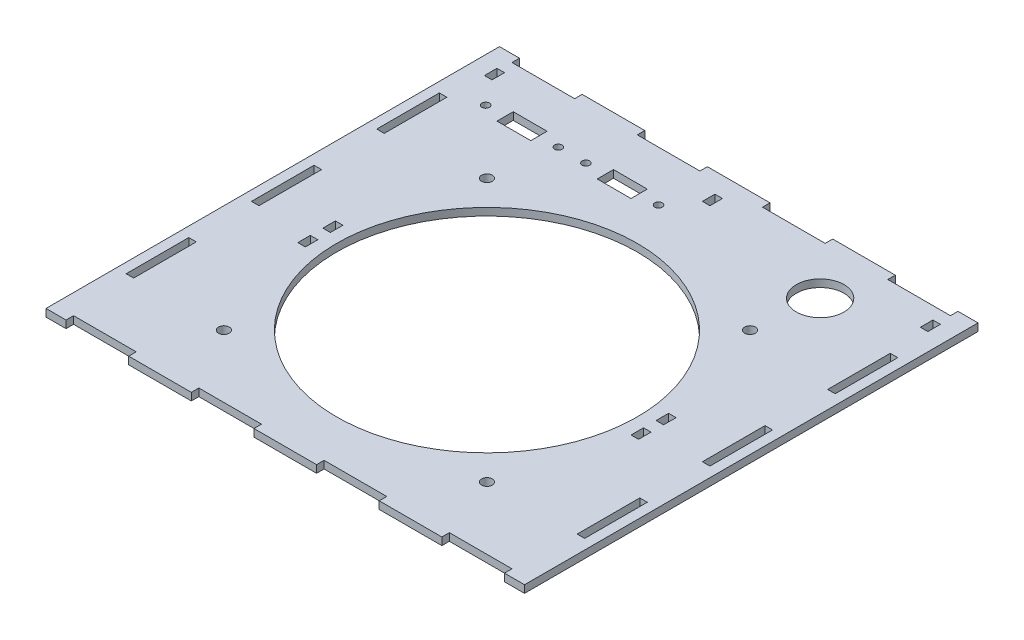
SolidWorks part; units mm, degrees
material "Buk"
ref_plane "Přední rovina" through (0, 0, 0) normal (0, 0, 1) x (1, 0, 0)
ref_plane "Horní rovina" through (0, 0, 0) normal (0, 1, 0) x (1, 0, 0)
ref_plane "Pravá rovina" through (0, 0, 0) normal (1, 0, 0) x (0, 0, -1)
sketch "Skica1" plane through (0, 0, 0) normal (0, 1, 0) x (1, 0, 0)
  line L0 (-95.5, -87.5) -> (95.5, 87.5) construction
  line L1 (-95.5, 87.5) -> (95.5, 87.5)
  line L2 (-95.5, 87.5) -> (-95.5, -87.5)
  line L3 (-95.5, -87.5) -> (95.5, -87.5)
  line L4 (95.5, 87.5) -> (95.5, -87.5)
  dimension "D1" = 175
  dimension "D2" = 191
extrude "Přidat vysunutím1" add sketch "Skica1" along normal blind 3
sketch "Skica13" plane through (0, 0, 0) normal (0, 1, 0) x (1, 0, 0)
  line L0 (95.5, 87.5) -> (-95.5, 87.5) construction
  line L1 (-62.5, 87.5) -> (-37.5, 87.5)
  line L2 (-62.5, 87.5) -> (-62.5, 90.5)
  line L3 (-62.5, 90.5) -> (-37.5, 90.5)
  line L4 (-37.5, 87.5) -> (-37.5, 90.5)
  line L6 (0, 0) -> (0, 52.1554) construction
  line L7 (-12.5, 87.5) -> (12.5, 87.5)
  line L8 (-12.5, 87.5) -> (-12.5, 90.5)
  line L9 (-12.5, 90.5) -> (12.5, 90.5)
  line L10 (12.5, 87.5) -> (12.5, 90.5)
  line L11 (37.5, 87.5) -> (62.5, 87.5)
  line L12 (37.5, 87.5) -> (37.5, 90.5)
  line L13 (37.5, 90.5) -> (62.5, 90.5)
  line L14 (62.5, 87.5) -> (62.5, 90.5)
  line L15 (-37.5, 90.5) -> (-12.5, 90.5) construction
  line L16 (-37.5, -90.5) -> (-12.5, -90.5) construction
  line L17 (62.5, -87.5) -> (62.5, -90.5)
  line L18 (37.5, -90.5) -> (62.5, -90.5)
  line L19 (37.5, -87.5) -> (37.5, -90.5)
  line L20 (37.5, -87.5) -> (62.5, -87.5)
  line L21 (12.5, -87.5) -> (12.5, -90.5)
  line L22 (-12.5, -90.5) -> (12.5, -90.5)
  line L23 (-12.5, -87.5) -> (-12.5, -90.5)
  line L24 (-12.5, -87.5) -> (12.5, -87.5)
  line L25 (-37.5, -87.5) -> (-37.5, -90.5)
  line L26 (-62.5, -90.5) -> (-37.5, -90.5)
  line L27 (-62.5, -87.5) -> (-62.5, -90.5)
  line L28 (-62.5, -87.5) -> (-37.5, -87.5)
  line L29 (-62.5, 90.5) -> (-87.5, 90.5) construction
  line L30 (-95.5, 87.5) -> (-87.5, 87.5)
  line L31 (-95.5, 87.5) -> (-95.5, 90.5)
  line L32 (-95.5, 90.5) -> (-87.5, 90.5)
  line L33 (-87.5, 87.5) -> (-87.5, 90.5)
  line L34 (95.5, -87.5) -> (87.5, -87.5)
  line L35 (87.5, 87.5) -> (87.5, 90.5)
  line L36 (95.5, -87.5) -> (95.5, -90.5)
  line L37 (95.5, -90.5) -> (87.5, -90.5)
  line L38 (95.5, 90.5) -> (87.5, 90.5)
  line L39 (95.5, 87.5) -> (95.5, 90.5)
  line L40 (95.5, 87.5) -> (87.5, 87.5)
  line L41 (87.5, -87.5) -> (87.5, -90.5)
  line L42 (-87.5, -87.5) -> (-87.5, -90.5)
  line L43 (-95.5, -90.5) -> (-87.5, -90.5)
  line L44 (-95.5, -87.5) -> (-95.5, -90.5)
  line L45 (-95.5, -87.5) -> (-87.5, -87.5)
  line L71 (0, 0) -> (-249.3085, 0) construction
  dimension "D1" = 25
  dimension "D2" = 3
  dimension "D3" = 3
extrude "Přidat vysunutím5" add sketch "Skica13" along normal up to surface (3 mm away) up to face at (0, 3, 0)
sketch "Skica14" plane through (0, 0, 0) normal (0, 1, 0) x (1, 0, 0)
  line L0 (95.5, -90.5) -> (95.5, 90.5) construction
  line L1 (85.5, 82.5) -> (88.5, 82.5)
  line L2 (85.5, 82.5) -> (85.5, 77.5)
  line L3 (85.5, 77.5) -> (88.5, 77.5)
  line L4 (88.5, 82.5) -> (88.5, 77.5)
  line L6 (87.5, 87.5) -> (62.5, 87.5) construction
  line L7 (-1.5, 82.5) -> (1.5, 82.5)
  line L8 (-1.5, 82.5) -> (-1.5, 77.5)
  line L9 (-1.5, 77.5) -> (1.5, 77.5)
  line L10 (1.5, 82.5) -> (1.5, 77.5)
  line L12 (0, 0) -> (0, 114.4854) construction
  line L17 (-88.5, 82.5) -> (-88.5, 77.5)
  line L18 (-85.5, 77.5) -> (-88.5, 77.5)
  line L19 (-85.5, 82.5) -> (-85.5, 77.5)
  line L20 (-85.5, 82.5) -> (-88.5, 82.5)
  dimension "D1" = 7
  dimension "D2" = 3
  dimension "D3" = 5
  dimension "D4" = 5
extrude "Odebrat vysunutím7" cut sketch "Skica14" along normal through all
sketch "Skica15" plane through (0, 0, 0) normal (0, 1, 0) x (1, 0, 0)
  line L1 (-91.5, 62.5) -> (-88.5, 62.5)
  line L2 (-91.5, 62.5) -> (-91.5, 37.5)
  line L3 (-91.5, 37.5) -> (-88.5, 37.5)
  line L4 (-88.5, 62.5) -> (-88.5, 37.5)
  line L5 (-95.5, 90.5) -> (-95.5, -90.5) construction
  line L6 (-62.5, 90.5) -> (-62.5, 87.5) construction
  line L8 (-91.5, 62.5) -> (-91.5, 87.5) construction
  line L9 (-62.5, 87.5) -> (-87.5, 87.5) construction
  line L10 (-91.5, 12.5) -> (-88.5, 12.5)
  line L11 (-91.5, 12.5) -> (-91.5, -12.5)
  line L12 (-91.5, -12.5) -> (-88.5, -12.5)
  line L13 (-88.5, 12.5) -> (-88.5, -12.5)
  line L14 (-91.5, -37.5) -> (-88.5, -37.5)
  line L15 (-91.5, -37.5) -> (-91.5, -62.5)
  line L16 (-91.5, -62.5) -> (-88.5, -62.5)
  line L17 (-88.5, -37.5) -> (-88.5, -62.5)
  line L18 (-91.5, 37.5) -> (-91.5, 12.5) construction
  line L19 (91.5, 37.5) -> (91.5, 12.5) construction
  line L20 (91.5, 62.5) -> (91.5, 87.5) construction
  line L21 (88.5, -37.5) -> (88.5, -62.5)
  line L22 (91.5, -62.5) -> (88.5, -62.5)
  line L23 (91.5, -37.5) -> (91.5, -62.5)
  line L24 (91.5, -37.5) -> (88.5, -37.5)
  line L25 (88.5, 12.5) -> (88.5, -12.5)
  line L26 (91.5, -12.5) -> (88.5, -12.5)
  line L27 (91.5, 12.5) -> (91.5, -12.5)
  line L28 (91.5, 12.5) -> (88.5, 12.5)
  line L29 (88.5, 62.5) -> (88.5, 37.5)
  line L30 (91.5, 37.5) -> (88.5, 37.5)
  line L31 (91.5, 62.5) -> (91.5, 37.5)
  line L32 (91.5, 62.5) -> (88.5, 62.5)
  line L73 (0, 0) -> (0, 107.6413) construction
  dimension "D1" = 25
  dimension "D2" = 4
  dimension "D3" = 3
extrude "Odebrat vysunutím8" cut sketch "Skica15" along normal through all
sketch "Skica16" plane through (0, 0, 0) normal (0, 1, 0) x (1, 0, 0)
  line L0 (-65, 0) -> (65, 0) construction
  line L2 (-65, -2.5) -> (-68, -2.5)
  line L3 (-65, -2.5) -> (-65, -7.5)
  line L4 (-65, -7.5) -> (-68, -7.5)
  line L5 (-68, -2.5) -> (-68, -7.5)
  line L6 (-65, -7.5) -> (-65, -12.5) construction
  line L7 (-87.5, -87.5) -> (-62.5, -87.5) construction
  line L10 (-65, -12.5) -> (-68, -12.5)
  line L11 (-65, -12.5) -> (-65, -17.5)
  line L12 (-65, -17.5) -> (-68, -17.5)
  line L13 (-68, -12.5) -> (-68, -17.5)
  line L14 (0, 0) -> (0, -24.7218) construction
  line L15 (65, -7.5) -> (65, -12.5) construction
  line L16 (68, -12.5) -> (68, -17.5)
  line L17 (65, -17.5) -> (68, -17.5)
  line L18 (65, -12.5) -> (65, -17.5)
  line L19 (65, -12.5) -> (68, -12.5)
  line L20 (68, -2.5) -> (68, -7.5)
  line L21 (65, -7.5) -> (68, -7.5)
  line L22 (65, -2.5) -> (65, -7.5)
  line L23 (65, -2.5) -> (68, -2.5)
  line L24 (-91.5, 12.5) -> (-88.5, 12.5) construction
  dimension "D1" = 130
  dimension "D2" = 85
  dimension "D3" = 5
extrude "Odebrat vysunutím9" cut sketch "Skica16" along normal through all
sketch "Skica4" plane through (0, 0, 0) normal (0, 1, 0) x (1, 0, 0)
  line L0 (0, 0) -> (0, 50) construction
  line L1 (-60, 50) -> (60, 50) construction
  line L2 (-60, 50) -> (-60, -70) construction
  line L3 (-60, -70) -> (60, -70) construction
  line L4 (60, 50) -> (60, -70) construction
  line L5 (-60, -70) -> (60, 50) construction
  line L6 (-60, -10) -> (60, -10) construction
  line L7 (60, -70) -> (-60, 50) construction
  line L9 (-68, -2.5) -> (-65, -2.5) construction
  line L10 (-65, -17.5) -> (-68, -17.5) construction
  circle A0 centre (-52.5, -62.5) radius 2.15
  circle A1 centre (52.5, 42.5) radius 2.15
  circle A2 centre (0, -10) radius 60
  circle A3 centre (-52.5, 42.5) radius 2.15
  circle A4 centre (52.5, -62.5) radius 2.15
  dimension "D2" = 105
  dimension "D4" = 4.3
  dimension "D5" = 120
  dimension "D1" = 120
extrude "Odebrat vysunutím5" cut sketch "Skica4" along normal through all
sketch "Skica5" plane through (0, 0, 0) normal (0, 1, 0) x (1, 0, 0)
  line L0 (95.5, -90.5) -> (95.5, 90.5) construction
  line L1 (87.5, 87.5) -> (62.5, 87.5) construction
  circle A0 centre (55.5, 67.5) radius 9.5
  circle A1 centre (55.5, 67.5) radius 11 construction
  dimension "D1" = 19
  dimension "D2" = 22
  dimension "D4" = 20
  dimension "D3" = 40
extrude "Odebrat vysunutím6" cut sketch "Skica5" along normal through all
sketch "Skica17" plane through (0, 0, 0) normal (0, 1, 0) x (1, 0, 0)
  line L0 (-78, 67.5) -> (-49, 67.5) construction
  line L1 (-63.5, 67.5) -> (-63.5, 62.0039) construction
  line L2 (-70.25, 70.75) -> (-56.75, 70.75)
  line L3 (-70.25, 70.75) -> (-70.25, 64.25)
  line L4 (-70.25, 64.25) -> (-56.75, 64.25)
  line L5 (-56.75, 70.75) -> (-56.75, 64.25)
  line L6 (-30.25, 70.75) -> (-16.75, 70.75)
  line L7 (-30.25, 70.75) -> (-30.25, 64.25)
  line L8 (-30.25, 64.25) -> (-16.75, 64.25)
  line L9 (-16.75, 70.75) -> (-16.75, 64.25)
  line L10 (-38, 67.5) -> (-9, 67.5) construction
  line L11 (-23.5, 67.5) -> (-23.5, 62.0039) construction
  line L13 (-43.5, 56.9694) -> (-43.5, 79.8624) construction
  line L14 (-85.5, 82.5) -> (-85.5, 77.5) construction
  line L15 (-1.5, 77.5) -> (-1.5, 82.5) construction
  circle A0 centre (-78, 67.5) radius 1.5
  circle A1 centre (-49, 67.5) radius 1.5
  circle A2 centre (-38, 67.5) radius 1.5
  circle A3 centre (-9, 67.5) radius 1.5
  circle A5 centre (55.5, 67.5) radius 9.5 construction
  point P22 (55.5, 67.5)
  dimension "D1" = 29
  dimension "D2" = 3
  dimension "D6" = 40
  dimension "D3" = 13.5
  dimension "D4" = 6.5
  dimension "D5" = 2
extrude "Odebrat vysunutím10" cut sketch "Skica17" along normal through all
